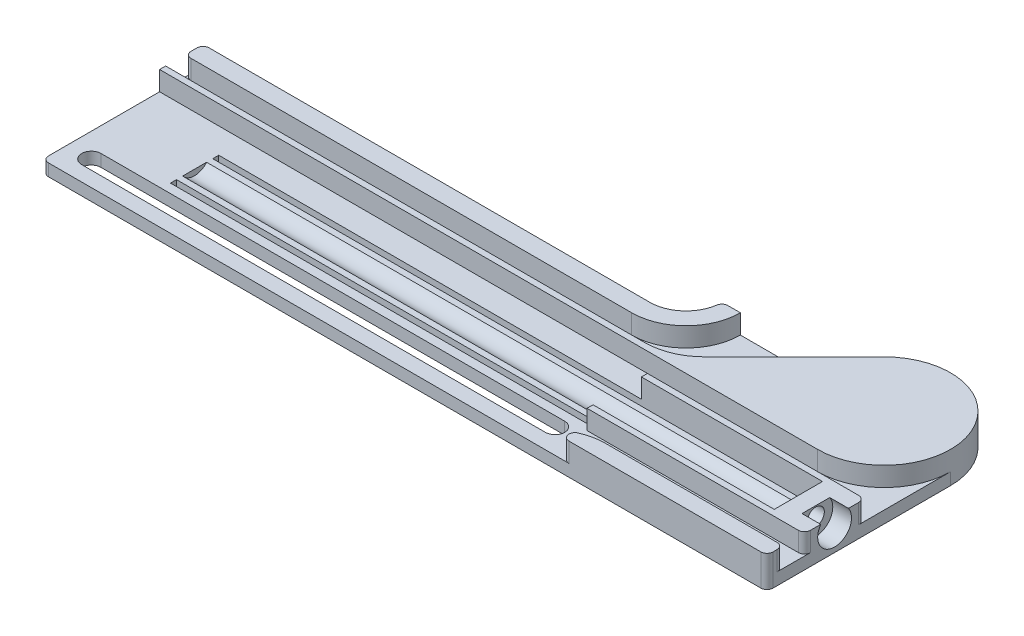
SolidWorks part; units mm, degrees
ref_plane "Front Plane" through (0, 0, 0) normal (0, 0, 1) x (1, 0, 0)
ref_plane "Top Plane" through (0, 0, 0) normal (0, 1, 0) x (1, 0, 0)
ref_plane "Right Plane" through (0, 0, 0) normal (1, 0, 0) x (0, 0, -1)
sketch "Sketch1" plane through (0, 0, 0) normal (0, 1, 0) x (1, 0, 0)
  line L0 (60, 19.3) -> (20, 19.3)
  line L3 (-60, 13.3) -> (-60, -13.3)
  line L4 (-60, -13.3) -> (60, -13.3)
  line L5 (60, -13.3) -> (60, 19.3)
  line L6 (-60, 10.3) -> (14, 10.3)
  line L7 (-60, 13.3) -> (14, 13.3)
  line L8 (-60, 6.1) -> (60, 6.1)
  line L9 (60, 2.9) -> (-60, 2.9)
  line L10 (-60, 7.1) -> (60, 7.1)
  line L11 (-60, 1.9) -> (60, 1.9)
  line L12 (-60, -6.1) -> (60, -6.1)
  line L13 (-60, -7.1) -> (60, -7.1)
  line L14 (-60, -10.3) -> (60, -10.3)
  arc A0 (14, 13.3) -> (20, 19.3) centre (14, 19.3) ccw
  arc A1 (14, 10.3) -> (23, 19.3) centre (14, 19.3) ccw
  point P7 (-60, 0)
  point P8 (0, -13.3)
  dimension "D1" = 120
  dimension "D3" = 6
  dimension "D4" = 80
  dimension "D5" = 3
  dimension "D6" = 3.2
  dimension "D7" = 3.2
  dimension "D8" = 1
  dimension "D9" = 1
  dimension "D10" = 8
  dimension "D11" = 1
  dimension "D12" = 3.2
  dimension "D13" = 3
sketch "Sketch4" plane through (0, 0, 0) normal (0, 1, 0) x (1, 0, 0)
  line L0 (-60, -13.3) -> (60, -13.3) construction
  line L1 (60, -13.3) -> (60, 19.3) construction
  line L2 (60, 19.3) -> (20, 19.3) construction
  line L3 (-60, 13.3) -> (14, 13.3) construction
  line L4 (-60, 13.3) -> (-60, -13.3) construction
  line L5 (-60, -13.3) -> (60, -13.3)
  line L6 (60, -13.3) -> (60, 19.3)
  line L7 (60, 19.3) -> (20, 19.3)
  line L8 (-60, 13.3) -> (14, 13.3)
  line L9 (-60, 13.3) -> (-60, -13.3)
  arc A0 (14, 13.3) -> (20, 19.3) centre (14, 19.3) ccw construction
  arc A1 (14, 13.3) -> (20, 19.3) centre (14, 19.3) ccw
extrude "Boss-Extrude2" add sketch "Sketch4" against normal blind 2
sketch "Sketch5" plane through (0, 0, 0) normal (0, 1, 0) x (1, 0, 0)
  line L0 (-60, 7.1) -> (60, 7.1) construction
  line L1 (60, 19.3) -> (20, 19.3) construction
  line L2 (23.4437, 7.1) -> (41.2218, 24.8782)
  line L4 (-60, 6.1) -> (60, 6.1) construction
  line L5 (60, -13.3) -> (60, 19.3) construction
  line L6 (23.4437, 7.1) -> (-60, 7.1)
  line L7 (-60, 7.1) -> (-60, 6.1)
  line L8 (-60, 6.1) -> (49, 6.1)
  arc A0 (14, 7.1) -> (26.2, 19.3) centre (14, 19.3) ccw construction
  arc A1 (49, 6.1) -> (41.2218, 24.8782) centre (49, 17.1) ccw
  point P7 (0, 0)
  point P8 (40.9167, 24.5606)
  dimension "D1" = 22
  dimension "D3" = 45
extrude "Boss-Extrude3" add sketch "Sketch5" along normal blind 3.2
sketch "Sketch6" plane through (0, 0, 0) normal (0, 1, 0) x (1, 0, 0)
  line L0 (-60, 10.3) -> (14, 10.3) construction
  line L1 (-60, 13.3) -> (14, 13.3) construction
  line L2 (-60, 10.3) -> (14, 10.3)
  line L3 (-60, 13.3) -> (14, 13.3)
  line L4 (20, 19.3) -> (23, 19.3)
  line L5 (-60, 10.3) -> (-60, 13.3)
  arc A0 (14, 10.3) -> (23, 19.3) centre (14, 19.3) ccw construction
  arc A1 (14, 13.3) -> (20, 19.3) centre (14, 19.3) ccw construction
  arc A2 (14, 10.3) -> (23, 19.3) centre (14, 19.3) ccw
  arc A3 (14, 13.3) -> (20, 19.3) centre (14, 19.3) ccw
extrude "Boss-Extrude4" add sketch "Sketch6" along normal blind 3.2
sketch "Sketch8" plane through (60, 0, 0) normal (1, 0, 0) x (0, 0, -1)
  line L0 (1.9, 0) -> (-6.1, 0) construction
  circle A0 centre (-2.1, 1.6) radius 2.8
  point P7 (-2.1, 0)
  dimension "D1" = 5.6
  dimension "D2" = 1.6
sketch "Sketch9" plane through (60, 0, 0) normal (1, 0, 0) x (0, 0, -1)
  line L0 (2.9, 0) -> (2.9, 3.2)
  line L2 (2.9, 3.2) -> (-7.1, 3.2)
  line L3 (-7.1, 3.2) -> (-7.1, 0)
  line L4 (2.9, 0) -> (-7.1, 0)
  point P2 (0, 0)
  dimension "D1" = 3.2
extrude "Boss-Extrude5" add sketch "Sketch9" against normal blind 6 contours L0 L2 L3 L4
ref_plane "Plane1" through (0, 0, 2.1) normal (0, 0, 1) x (1, 0, 0)
extrude "Cut-Extrude1" cut sketch "Sketch8" against normal blind 3.1
sketch "Sketch10" plane through (56.9, 0, 0) normal (1, 0, 0) x (0, 0, -1)
  circle A0 centre (-2.1, 1.6) radius 1.4
  dimension "D1" = 2.8
extrude "Cut-Extrude2" cut sketch "Sketch10" against normal through all
sketch "Sketch11" plane through (54, 0, 0) normal (-1, 0, 0) x (0, 0, 1)
  circle A0 centre (2.1, 1.6) radius 2.55
  dimension "D1" = 5.1
extrude "Cut-Extrude3" cut sketch "Sketch11" along normal blind 100
sketch "Sketch12" plane through (0, 0, 0) normal (0, 1, 0) x (1, 0, 0)
  line L0 (-60, 1.9) -> (60, 1.9) construction
  line L1 (54, 2.9) -> (24, 2.9)
  line L2 (54, 2.9) -> (54, 1.9)
  line L3 (54, 1.9) -> (24, 1.9)
  line L4 (24, 2.9) -> (24, 1.9)
  point P5 (19.0415, 1.13)
  point P6 (0, 0)
  dimension "D1" = 30
extrude "Boss-Extrude6" add sketch "Sketch12" along normal blind 3.2
sketch "Sketch13" plane through (0, 0, 0) normal (0, 1, 0) x (1, 0, 0)
  line L0 (54, 1.9) -> (54, -0.1144) construction
  line L1 (-46, 1.9) -> (54, 1.9)
  line L2 (-46, 1.9) -> (-46, 0.9)
  line L3 (-46, 0.9) -> (54, 0.9)
  line L4 (54, 1.9) -> (54, 0.9)
  line L5 (-60, 1.9) -> (60, 1.9) construction
  dimension "D1" = 1
  dimension "D2" = 100
extrude "Cut-Extrude4" cut sketch "Sketch13" against normal through all
mirror "Mirror1" about plane through (0, 0, 2.1) normal (0, 0, 1) of "Boss-Extrude6", "Cut-Extrude4"
sketch "Sketch14" plane through (0, 0, 0) normal (0, 1, 0) x (1, 0, 0)
  line L0 (60, -10.6) -> (30.5184, -10.6)
  line L2 (-60, -13.3) -> (60, -13.3) construction
  line L3 (24, -13.3) -> (60, -13.3)
  line L4 (60, -13.3) -> (60, -10.6)
  line L5 (24, -13.3) -> (27, -10.3) construction
  line L6 (-60, -10.3) -> (60, -10.3) construction
  line L7 (24, -7.1) -> (60, -7.1) construction
  arc A0 (30.5184, -10.6) -> (24, -13.3) centre (30.5184, -19.8184) ccw
  point P5 (0, 0)
  dimension "D2" = 45
  dimension "D1" = 36
  dimension "D3" = 3.5
extrude "Boss-Extrude7" add sketch "Sketch14" along normal blind 3.2
sketch "Sketch15" plane through (0, 0, 0) normal (0, 1, 0) x (1, 0, 0)
  line L0 (-56, -9.2) -> (20.8, -9.2) construction
  line L1 (-56, -7.6) -> (20.8, -7.6)
  line L2 (-56, -10.8) -> (20.8, -10.8)
  line L3 (-46, -0.1144) -> (-46, -4.0856) construction
  line L4 (-46, -0.1144) -> (-46, -4.0856) construction
  arc A0 (-56, -7.6) -> (-56, -10.8) centre (-56, -9.2) ccw
  arc A1 (20.8, -10.8) -> (20.8, -7.6) centre (20.8, -9.2) ccw
  point P2 (-17.6, -9.2)
  point P9 (-46, -2.1)
  point P10 (15.7483, -9.2)
  dimension "D1" = 3.2
  dimension "D2" = 80
  dimension "D3" = 7.1
  dimension "D4" = 10
extrude "Cut-Extrude5" cut sketch "Sketch15" against normal through all
fillet "Fillet1" radius 10 1 edges at (23.4437, 1.6, -7.1)
sketch "Sketch16" plane through (0, 0, 0) normal (0, -1, 0) x (1, 0, 0)
  line L2 (59.7778, -19.3) -> (35.6437, -19.3)
  line L3 (35.6437, -19.3) -> (41.2218, -24.8782)
  line L4 (59.7778, -19.3) -> (35.6437, -19.3)
  line L5 (35.6437, -19.3) -> (41.2218, -24.8782)
  arc A1 (41.2218, -24.8782) -> (59.7778, -19.3) centre (49, -17.1) ccw
  arc A2 (41.2218, -24.8782) -> (59.7778, -19.3) centre (49, -17.1) ccw
  dimension "D1" = 0
extrude "Boss-Extrude8" add sketch "Sketch16" along normal up to surface (2 mm away) up to face at (-17.6, -2, 9.2)
sketch "Sketch17" plane through (0, 0, 0) normal (0, 1, 0) x (1, 0, 0)
  line L2 (60, 17.1) -> (60, 19.3)
  line L3 (60, 19.3) -> (59.7778, 19.3)
  line L4 (60, 17.1) -> (60, 19.3)
  line L5 (60, 19.3) -> (59.7778, 19.3)
  arc A1 (60, 17.1) -> (59.7778, 19.3) centre (49, 17.1) ccw
  arc A2 (60, 17.1) -> (59.7778, 19.3) centre (49, 17.1) ccw
  dimension "D1" = 0
extrude "Cut-Extrude6" cut sketch "Sketch17" against normal through all
fillet "Fillet2" radius 1 10 edges at (-60, -1, 13.3) (35.6437, -1, -19.3) (20, 0.6, -19.3) (60, 0.6, 13.3) (-60, 0.6, -13.3) (-60, 1.6, -10.3) (60, 1.6, 10.6) (60, 1.6, 7.1) (60, 1.6, -2.9) (24, 1.6, 13.3)
equation "\"cable_OD\"= 3.2mm"
equation "\"D7@Sketch1\"=\"cable_OD\""
equation "\"D6@Sketch1\"=\"cable_OD\""
equation "\"D12@Sketch1\"=\"cable_OD\""
equation "\"D1@Boss-Extrude3\"=\"cable_OD\""
equation "\"D1@Boss-Extrude4\"=\"cable_OD\""
equation "\"D2@Sketch8\"=\"cable_OD\"/2"
equation "\"D1@Sketch9\"=\"cable_OD\""
equation "\"D1@Boss-Extrude6\"=\"cable_OD\""
equation "\"D1@Boss-Extrude7\"=\"cable_OD\""
